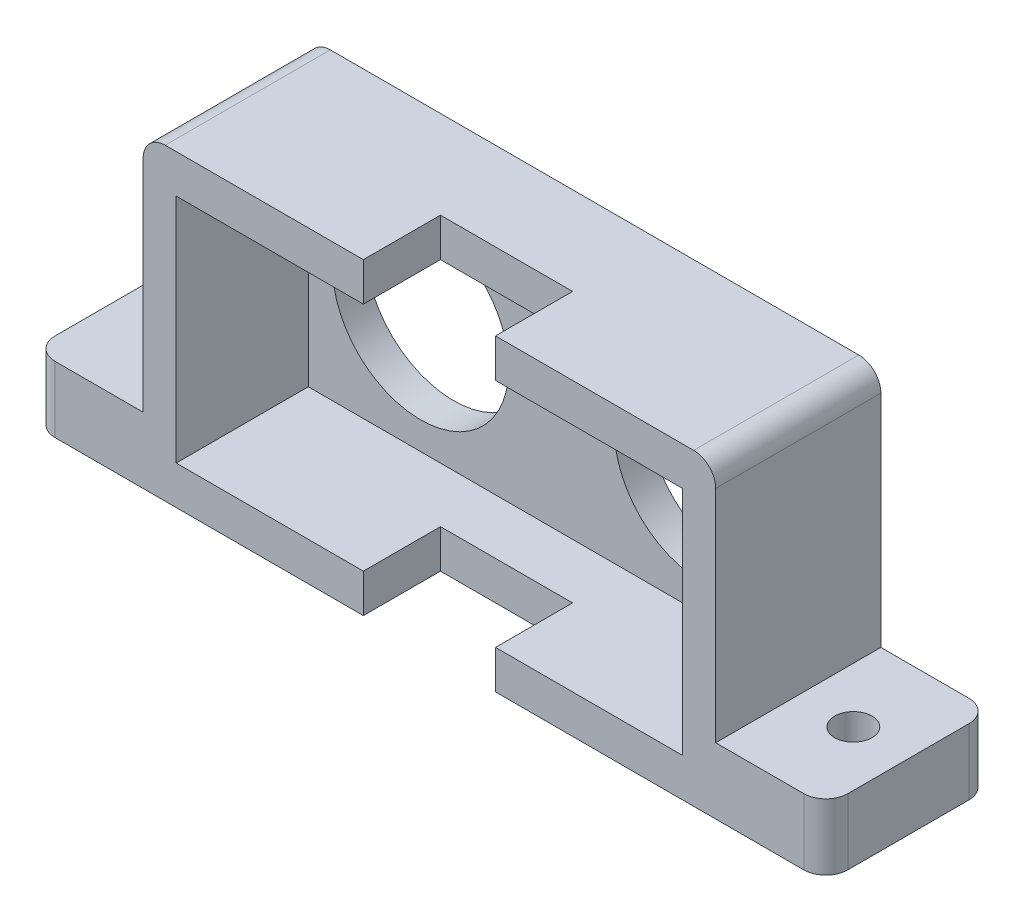
SolidWorks part; units mm, degrees
material "PLA"
ref_plane "Plan de face" through (0, 0, 0) normal (0, 0, 1) x (1, 0, 0)
ref_plane "Plan de dessus" through (0, 0, 0) normal (0, 1, 0) x (1, 0, 0)
ref_plane "Plan de droite" through (0, 0, 0) normal (1, 0, 0) x (0, 0, -1)
sketch "Esquisse1" plane through (0, 0, 0) normal (0, 0, 1) x (1, 0, 0)
  line L0 (36, 0) -> (-36, 0)
  line L1 (-36, 0) -> (36, 0) construction
  line L2 (-36, 0) -> (-36, 28) construction
  line L3 (-36, 28) -> (36, 28) construction
  line L4 (36, 0) -> (36, 28) construction
  line L5 (-36, 0) -> (-36, 6)
  line L6 (-36, 6) -> (-26, 6)
  line L7 (-26, 6) -> (-26, 28)
  line L8 (-26, 28) -> (26, 28)
  line L9 (26, 28) -> (26, 6)
  line L10 (26, 6) -> (36, 6)
  line L11 (36, 6) -> (36, 0)
  point P4 (0, 0)
  dimension "D1" = 72
  dimension "D2" = 28
  dimension "D3" = 10
  dimension "D4" = 6
  dimension "D5" = 6
  dimension "D6" = 10
extrude "Boss.-Extru.1" add sketch "Esquisse1" along normal blind 15
sketch "Esquisse2" plane through (0, 0, 15) normal (0, 0, 1) x (1, 0, 0)
  line L0 (0, 0) -> (0, 28) construction
  line L1 (-23, 24.5) -> (23, 24.5) construction
  line L2 (-23, 24.5) -> (-23, 3.5) construction
  line L3 (-23, 3.5) -> (23, 3.5) construction
  line L4 (23, 24.5) -> (23, 3.5) construction
  line L5 (26, 28) -> (-26, 28) construction
  line L6 (-23, 14) -> (23, 14) construction
  line L9 (-23, 24.5) -> (23, 24.5)
  line L10 (-23, 24.5) -> (-23, 3.5)
  line L11 (-23, 3.5) -> (23, 3.5)
  line L12 (23, 24.5) -> (23, 3.5)
  point P4 (0, 3.5)
  point P9 (0, 14)
  dimension "D1" = 46
  dimension "D2" = 21
extrude "Enlèv. mat.-Extru.1" cut sketch "Esquisse2" against normal offset from surface (12 mm away) 3 up to face at (0, 10, 0)
sketch "Esquisse4" plane through (0, 0, 3) normal (0, 0, 1) x (1, 0, 0)
  line L0 (-4.8, 14) -> (4.8, 14) construction
  line L1 (0, 0) -> (0, 28) construction
  line L2 (-36, 0) -> (36, 0) construction
  line L3 (26, 28) -> (-26, 28) construction
  circle A0 centre (-12.8, 14) radius 8
  circle A1 centre (12.8, 14) radius 8
  point P12 (0, 14)
  point P13 (0, 14)
  dimension "D1" = 16
  dimension "D2" = 16
  dimension "D3" = 9.6
extrude "Enlèv. mat.-Extru.2" cut sketch "Esquisse4" against normal blind 3
sketch "Esquisse5" plane through (0, 0, 0) normal (0, -1, 0) x (1, 0, 0)
  line L0 (-36, 15) -> (36, 15) construction
  line L1 (-6, 15) -> (6, 15)
  line L2 (-6, 15) -> (-6, 8)
  line L3 (-6, 8) -> (6, 8)
  line L4 (6, 15) -> (6, 8)
  line L5 (0, 0) -> (0, 15) construction
  point P9 (0, 15)
  dimension "D1" = 12
  dimension "D2" = 7
extrude "Enlèv. mat.-Extru.3" cut sketch "Esquisse5" against normal up to surface (28 mm away) up to face at (0, 28, 7.5)
fillet "Congé1" radius 2 6 edges at (-36, 3, 0) (36, 3, 0) (36, 3, 15) (-36, 3, 15) (-26, 28, 7.5) (26, 28, 7.5)
sketch "Esquisse6" plane through (0, 6, 0) normal (0, 1, 0) x (1, 0, 0)
  line L0 (-36, -7.5) -> (36, -7.5) construction
  line L1 (-36, -13) -> (-36, -2) construction
  line L2 (36, -13) -> (36, -2) construction
  circle A0 centre (31, -7.5) radius 1
  circle A1 centre (-31, -7.5) radius 1
  dimension "D1" = 2
  dimension "D2" = 2
  dimension "D3" = 5
  dimension "D4" = 5
hole_wizard "Dégagement M31" positions "Esquisse7" profile "Esquisse9" hole size "M3" standard "ISO" end condition through all
sketch "Esquisse7" plane through (0, 6, 0) normal (0, 1, 0) x (1, 0, 0)
  point P0 (-31, -7.5)
  point P3 (31, -7.5)
sketch "Esquisse9" plane through (-31, 6, 7.5) normal (1, 0, 0) x (0, 0, 1)
  line L0 (0, 0) -> (0, 6)
  line L1 (0, 6) -> (1.7, 6)
  line L2 (1.7, 6) -> (1.7, 0)
  line L5 (1.7, 0) -> (0, 0)
  line L11 (0, -6.35) -> (0, 107.95) construction
  dimension "Diamètre du perçage jusqu'au prochain" = 3.4
  dimension "Profondeur du perçage jusqu'au prochain" = 6
